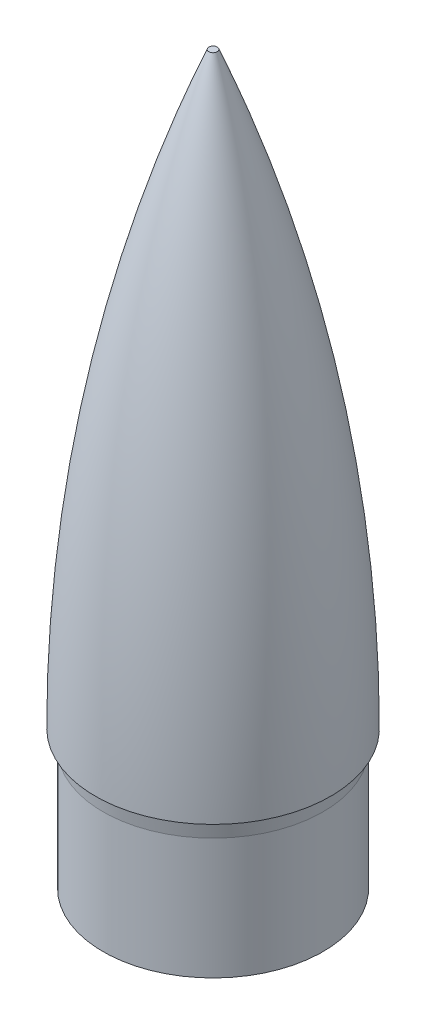
SolidWorks part; units mm, degrees
ref_plane "Front Plane" through (0, 0, 0) normal (0, 0, 1) x (1, 0, 0)
ref_plane "Top Plane" through (0, 0, 0) normal (0, 1, 0) x (1, 0, 0)
ref_plane "Right Plane" through (0, 0, 0) normal (1, 0, 0) x (0, 0, -1)
sketch "Sketch1" plane through (0, 0, 0) normal (0, 0, 1) x (1, 0, 0)
  line L0 (17, 0) -> (16.25, 0)
  line L1 (16.25, 0) -> (15.9, -2.5)
  line L2 (15.9, -2.5) -> (15.9, -20)
  line L3 (15.9, -20) -> (15.1, -20)
  line L4 (15.1, -20) -> (15.1, 0)
  line L5 (0, -18.7) -> (0, 18.7) construction
  line L6 (-15.1, -20) -> (-15.1, 0) construction
  line L7 (-15.9, -20) -> (-15.1, -20) construction
  line L8 (-15.9, -2.5) -> (-15.9, -20) construction
  line L9 (-16.25, 0) -> (-15.9, -2.5) construction
  line L10 (-17, 0) -> (-16.25, 0) construction
  line L11 (0, 0) -> (0, 85) construction
  line L12 (0.6, 85) -> (0, 85)
  line L13 (0.5066, 80) -> (0, 80)
  line L14 (0, 80) -> (0, 85)
  arc A0 (17, 0) -> (0.6, 85) centre (-211.4744, 0) ccw
  arc A1 (-17, 0) -> (-0.6, 85) centre (211.4744, 0) cw construction
  arc A2 (15.1, 0) -> (0.5066, 80) centre (-211.4744, 0) ccw
  arc A3 (-15.1, 0) -> (-0.5066, 80) centre (211.4744, 0) cw construction
  dimension "D1" = 34
  dimension "D2" = 85
  dimension "D3" = 31.8
  dimension "D9" = 80
  dimension "D4" = 0.8
  dimension "D5" = 20
  dimension "D6" = 32.5
  dimension "D7" = 2.5
  dimension "D8" = 1.2
revolve "Revolve1" add sketch "Sketch1" angle 360 about L14
sketch "Sketch2" plane through (0, 0, 0) normal (0, 0, 1) x (1, 0, 0)
  line L0 (-15.5, -20) -> (15.5, -20)
  line L1 (-15.1, -20) -> (15.1, -20) construction
  line L2 (-15.9, -20) -> (15.9, -20) construction
  line L3 (15.5, -20) -> (15.5, 0)
  line L4 (-16.25, 0) -> (16.25, 0) construction
  line L5 (15.9, -20) -> (15.9, -2.5) construction
  line L6 (-0.5066, 80) -> (0.5066, 80) construction
  line L7 (0, -18.7) -> (0, 18.7) construction
  line L8 (-15.5, -20) -> (-15.5, 0)
  line L9 (-0.783, 80.4) -> (0.783, 80.4)
  arc A0 (15.5, 0) -> (0.783, 80.4) centre (-211.4744, 0) ccw
  arc A1 (17, 0) -> (0.6, 85) centre (-211.4744, 0) ccw construction
  arc A2 (-15.5, 0) -> (-0.783, 80.4) centre (211.4744, 0) cw
  point P33 (0, -20)
  dimension "D1" = 0.4
  dimension "D2" = 0.4
extrude "Boss-Extrude1" add sketch "Sketch2" along normal mid plane 2
sketch "Sketch3" plane through (0, 0, -1) normal (0, 0, -1) x (-1, 0, 0)
  line L11 (0, 18.7) -> (0, -18.7) construction
  line L13 (-9.9, -10) -> (-9.9, -20) construction
  line L14 (15.0669, -20) -> (-15.0669, -20) construction
  line L15 (-15.9, -2.5) -> (-15.9, -20) construction
  line L16 (-15.9, -20) -> (15.9, -20) construction
  circle A0 centre (6.9, -10) radius 3
  circle A1 centre (-6.9, -10) radius 3
  point P6 (-9.9968, -20)
  point P13 (-6.9, -7.2895)
  dimension "D1" = 6
  dimension "D2" = 6
  dimension "D3" = 10
extrude "Cut-Extrude1" cut sketch "Sketch3" against normal up to surface (2 mm away) up to face at (-0.0249, -29.6667, 1)
